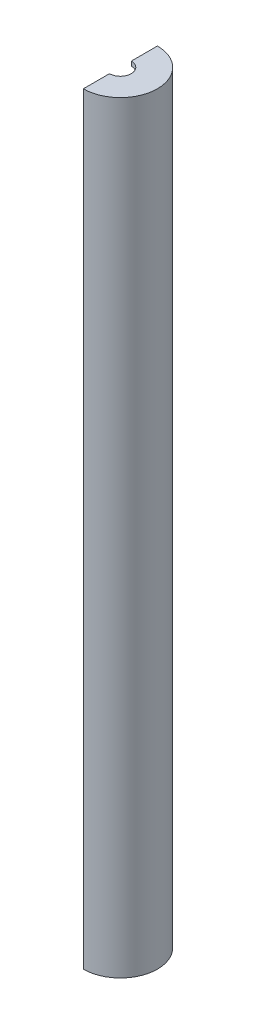
SolidWorks part; units mm, degrees
ref_plane "前视基准面" through (0, 0, 0) normal (0, 0, 1) x (1, 0, 0)
ref_plane "上视基准面" through (0, 0, 0) normal (0, 1, 0) x (1, 0, 0)
ref_plane "右视基准面" through (0, 0, 0) normal (1, 0, 0) x (0, 0, -1)
sketch "草图1" plane through (0, 0, 0) normal (0, 1, 0) x (1, 0, 0)
  line L0 (0, 17) -> (0, 15)
  line L1 (0, -15) -> (0, -17)
  arc A0 (0, -15) -> (0, 15) centre (0, 0) ccw
  arc A1 (0, -17) -> (0, 17) centre (0, 0) ccw
  dimension "D1" = 30
  dimension "D2" = 34
extrude "凸台-拉伸1" add sketch "草图1" along normal blind 350
sketch "草图2" plane through (0, 350, 0) normal (0, 1, 0) x (1, 0, 0)
  line L0 (0, 17) -> (0, 5)
  line L1 (0, -5) -> (0, -17)
  arc A0 (0, -17) -> (0, 17) centre (0, 0) ccw
  arc A1 (0, -5) -> (0, 5) centre (0, 0) ccw
  dimension "D1" = 10
extrude "凸台-拉伸2" add sketch "草图2" against normal blind 2
sketch "草图3" plane through (0, 0, 0) normal (0, -1, 0) x (1, 0, 0)
  line L0 (0, 17) -> (0, 5)
  line L1 (0, -5) -> (0, -17)
  arc A0 (0, -17) -> (0, 17) centre (0, 0) ccw
  arc A1 (0, -5) -> (0, 5) centre (0, 0) ccw
extrude "凸台-拉伸3" add sketch "草图3" against normal blind 2
